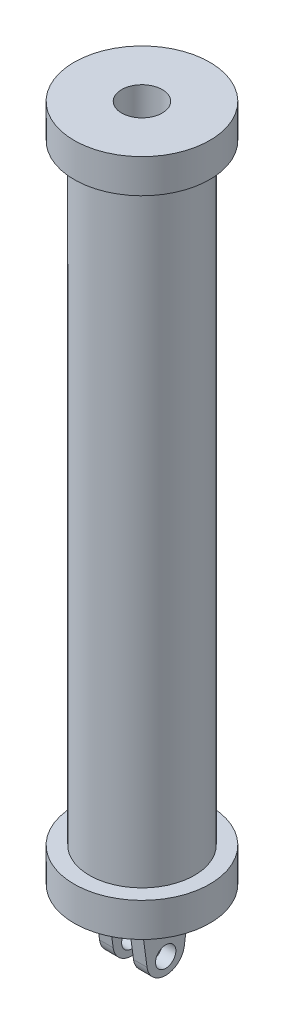
SolidWorks part; units mm, degrees
ref_plane "Front Plane" through (0, 0, 0) normal (0, 0, 1) x (1, 0, 0)
ref_plane "Top Plane" through (0, 0, 0) normal (0, 1, 0) x (1, 0, 0)
ref_plane "Right Plane" through (0, 0, 0) normal (1, 0, 0) x (0, 0, -1)
sketch "Sketch1" plane through (0, 0, 0) normal (0, 0, 1) x (1, 0, 0)
  line L0 (0, 0) -> (0, 5) construction
  line L1 (0, 100) -> (10, 100)
  line L2 (10, 100) -> (10, 95)
  line L3 (10, 0) -> (0, 0)
  line L4 (10, 95) -> (7.75, 95)
  line L5 (7.75, 95) -> (7.75, 5)
  line L6 (7.75, 5) -> (10, 5)
  line L7 (10, 5) -> (10, 0)
  line L8 (0, 100) -> (0, 95)
  line L9 (0, 95) -> (5, 95)
  line L10 (5, 95) -> (5, 5)
  line L11 (5, 5) -> (0, 5)
  line L12 (0, 95) -> (0, 100) construction
  line L13 (0, 5) -> (0, 0)
  dimension "D1" = 100
  dimension "D2" = 10
  dimension "D3" = 5
  dimension "D4" = 5
  dimension "D5" = 2.25
  dimension "D6" = 5
revolve "Revolve2" add sketch "Sketch1" angle 360 about L8
sketch "Sketch3" plane through (0, 100, 0) normal (0, 1, 0) x (1, 0, 0)
  circle A0 centre (0, 0) radius 3
  dimension "D1" = 6
extrude "Cut-Extrude1" cut sketch "Sketch3" against normal up to surface (5 mm away) up to face at (-10, 95, 0)
sketch "Sketch4" plane through (0, 0, 0) normal (0, -1, 0) x (1, 0, 0)
  line L0 (-1.5, 3.75) -> (-1.5, -3.75)
  line L1 (-3.5, -3.75) -> (3.5, -3.75)
  line L2 (-3.5, -3.75) -> (-3.5, 3.75)
  line L3 (-3.5, 3.75) -> (3.5, 3.75)
  line L4 (3.5, -3.75) -> (3.5, 3.75)
  line L5 (-3.5, -3.75) -> (3.5, 3.75) construction
  line L6 (-3.5, 3.75) -> (3.5, -3.75) construction
  line L7 (1.5, 3.75) -> (1.5, -3.75)
  point P0 (0, 0)
  dimension "D1" = 7
  dimension "D2" = 7.5
  dimension "D3" = 2
  dimension "D4" = 2
extrude "Boss-Extrude2" add sketch "Sketch4" along normal blind 10 contours L3 L2 L1 L0 | L3 L7 L1 L4
sketch "Sketch6" plane through (3.5, 0, 0) normal (1, 0, 0) x (0, 0, -1)
  line L0 (-3.75, 0) -> (-2.75, -7.5)
  line L1 (2.75, -7.5) -> (3.75, 0)
  line L7 (3.75, 0) -> (-3.75, 0)
  line L8 (-3.75, 0) -> (-3.75, -10)
  line L9 (-3.75, -10) -> (3.75, -10)
  line L10 (3.75, -10) -> (3.75, 0)
  line L12 (-3.75, 0) -> (-3.75, -10)
  line L13 (-3.75, -10) -> (3.75, -10)
  line L14 (3.75, -10) -> (3.75, 0)
  circle A0 centre (0, -7.5) radius 1.5
  arc A1 (-2.75, -7.5) -> (2.75, -7.5) centre (0, -7.1333) ccw
  dimension "D1" = 3
  dimension "D2" = 7.5
  dimension "D3" = 5.5
  dimension "D4" = 0
extrude "Cut-Extrude2" cut sketch "Sketch6" against normal blind 10
